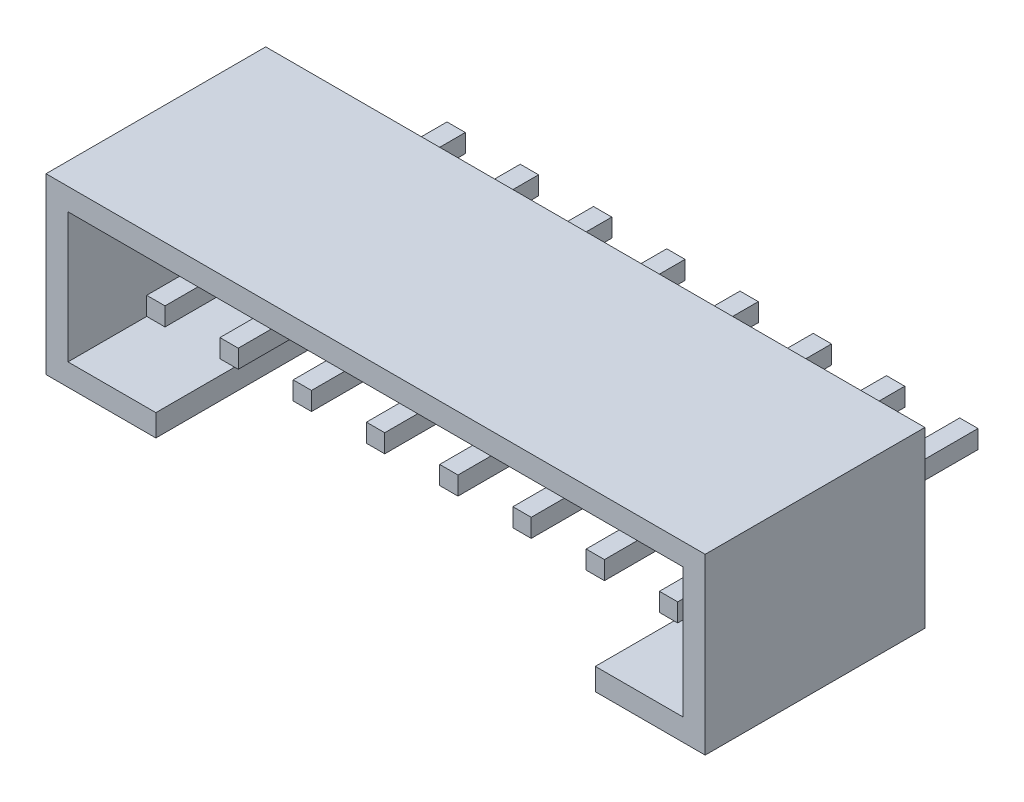
SolidWorks part; units mm, degrees
ref_plane "Front Plane" through (0, 0, 0) normal (0, 0, 1) x (1, 0, 0)
ref_plane "Top Plane" through (0, 0, 0) normal (0, 1, 0) x (1, 0, 0)
ref_plane "Right Plane" through (0, 0, 0) normal (1, 0, 0) x (0, 0, -1)
sketch "Sketch1" plane through (0, 0, 0) normal (0, 0, 1) x (1, 0, 0)
  line L1 (-9, 2.375) -> (9, 2.375)
  line L2 (-9, 2.375) -> (-9, -2.375)
  line L3 (-9, -2.375) -> (9, -2.375)
  line L4 (9, 2.375) -> (9, -2.375)
  line L5 (-9, 2.375) -> (9, -2.375) construction
  line L6 (-9, -2.375) -> (9, 2.375) construction
  point P0 (0, 0)
  dimension "D1" = 18
  dimension "D2" = 4.75
extrude "Boss-Extrude1" add sketch "Sketch1" along normal blind 1.8
sketch "Sketch2" plane through (0, 0, 1.8) normal (0, 0, 1) x (1, 0, 0)
  line L0 (-6, -2.375) -> (-6, -1.775)
  line L1 (-9, -2.375) -> (9, -2.375) construction
  line L2 (-6, -1.775) -> (-8.4, -1.775)
  line L3 (-8.4, -1.775) -> (-8.4, 1.775)
  line L4 (-8.4, 1.775) -> (8.4, 1.775)
  line L5 (0, 1.775) -> (0, 0) construction
  line L6 (-6, -2.375) -> (-9, -2.375)
  line L7 (-9, -2.375) -> (-9, 2.375)
  line L8 (-9, 2.375) -> (9, 2.375)
  line L9 (9, 2.375) -> (-9, 2.375) construction
  line L10 (9, -2.375) -> (9, 2.375)
  line L11 (6, -2.375) -> (9, -2.375)
  line L12 (6, -2.375) -> (6, -1.775)
  line L13 (6, -1.775) -> (8.4, -1.775)
  line L14 (8.4, -1.775) -> (8.4, 1.775)
  point P13 (-8.312, 1.775)
  point P22 (0, 2.375)
  dimension "D1" = 3
  dimension "D2" = 0.6
  dimension "D3" = 0.6
  dimension "D4" = 0.6
extrude "Boss-Extrude2" add sketch "Sketch2" along normal offset from surface (4.2 mm away) 6 up to face at (0, 0, 0)
sketch "Sketch3" plane through (0, 0, 1.8) normal (0, 0, 1) x (1, 0, 0)
  line L0 (-6, -2.375) -> (6, -2.375) construction
  line L1 (-7.25, -0.125) -> (-6.75, -0.125)
  line L2 (-7.25, -0.125) -> (-7.25, -0.625)
  line L3 (-7.25, -0.625) -> (-6.75, -0.625)
  line L4 (-6.75, -0.125) -> (-6.75, -0.625)
  point P4 (-7.25, -0.375)
  point P7 (-7, -0.625)
  dimension "D1" = 0.5
  dimension "D2" = 2
  dimension "D3" = 7
extrude "Boss-Extrude3" add sketch "Sketch3" along normal offset from surface 5 and the other way blind 5 up to face at (0, 0, 0)
pattern_linear "LPattern1" count 8 spacing 2 along (1, 0, 0) of "Boss-Extrude3"
